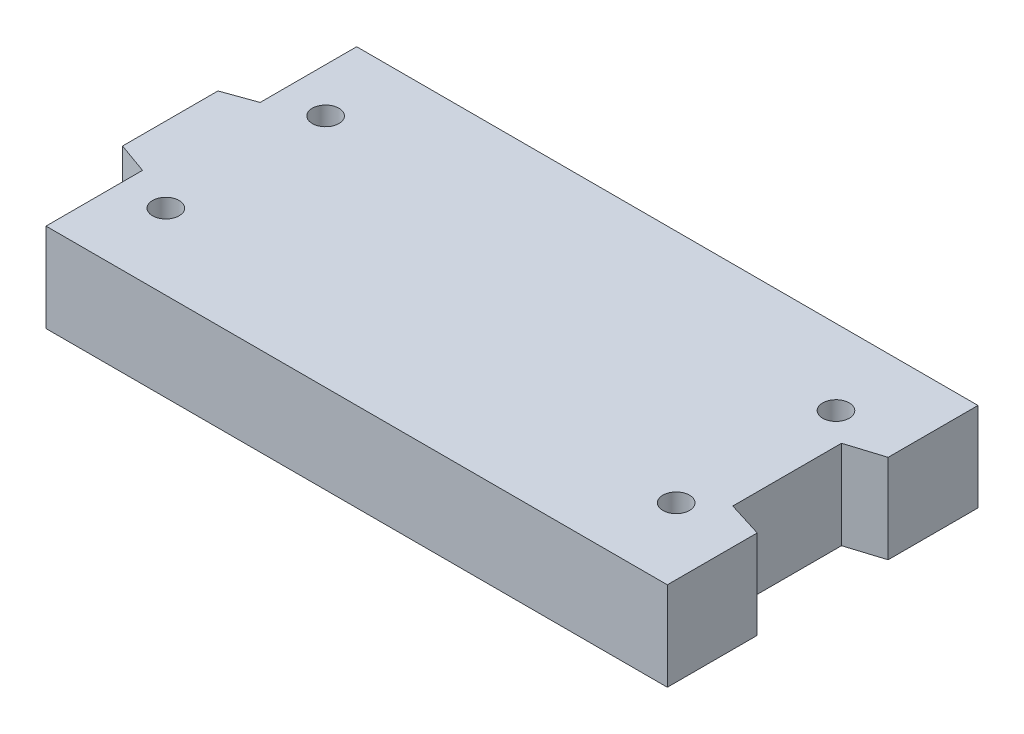
SolidWorks part; units mm, degrees
material "Carburized and nitrided special steel"
ref_plane "Piano frontale" through (0, 0, 0) normal (0, 0, 1) x (1, 0, 0)
ref_plane "Piano superiore" through (0, 0, 0) normal (0, 1, 0) x (1, 0, 0)
ref_plane "Piano destro" through (0, 0, 0) normal (1, 0, 0) x (0, 0, -1)
sketch "Schizzo2" plane through (0, 0, 0) normal (0, 1, 0) x (1, 0, 0)
  line L0 (-166.882, 0) -> (166.882, 0) construction
  line L1 (-162.6525, 21.5) -> (-162.6525, -21.5)
  line L2 (115.3475, 24.5) -> (115.3475, -24.5)
  line L3 (-144.6525, 70) -> (127.3475, 70)
  line L4 (131.3475, -29.5) -> (131.3475, -66)
  line L5 (-148.6525, -26.5) -> (-148.6525, -66)
  line L6 (-162.6525, 21.5) -> (-148.6525, 26.5)
  line L7 (115.3475, -24.5) -> (131.3475, -29.5)
  line L8 (115.3475, 24.5) -> (131.3475, 29.5)
  line L9 (-162.6525, -21.5) -> (-148.6525, -26.5)
  line L10 (-144.6525, -70) -> (127.3475, -70)
  line L11 (-148.6525, 26.5) -> (-148.6525, 66)
  line L12 (131.3475, 29.5) -> (131.3475, 66)
  line L13 (127.3475, 70) -> (131.3475, 70)
  line L14 (-148.6525, -66) -> (-148.6525, -70)
  line L15 (127.3475, -70) -> (131.3475, -70)
  line L16 (131.3475, -70) -> (131.3475, -66)
  line L17 (-144.6525, 70) -> (-148.6525, 70)
  line L18 (-148.6525, 70) -> (-148.6525, 66)
  line L19 (131.3475, 70) -> (131.3475, 66)
  line L20 (-148.6525, -70) -> (-144.6525, -70)
  point P1 (131.3475, 70)
  point P2 (-148.6525, 70)
  point P7 (-162.6525, 0)
  point P8 (131.3475, -70)
  point P13 (-148.6525, -70)
  point P15 (-162.6525, 0)
  point P17 (115.3475, 0)
  dimension "D1" = 70
  dimension "D2" = 26.5
  dimension "D3" = 21.5
  dimension "D4" = 280
  dimension "D5" = 16
  dimension "D6" = 24.5
  dimension "D7" = 29.5
  dimension "D8" = 14
extrude "Estrusione1" add sketch "Schizzo2" along normal blind 40
sketch "Schizzo5" plane through (0, 0, 0) normal (0, -1, 0) x (1, 0, 0)
  line L0 (-173.132, 0) -> (146.5535, 0) construction
  line L1 (-80.6525, 93.4302) -> (-80.6525, -110.732) construction
  line L4 (-148.6525, -70) -> (-148.6525, -26.5) construction
  circle A0 centre (-80.6525, 0) radius 40.25
  dimension "D1" = 68
extrude "Estrusione4" cut sketch "Schizzo5" against normal blind 12.5
draft "Sformo2" type of draft neutral plane draft angle 25 faces to draft 1 face at (-80.6525, 12.5, -40.25) neutral plane through (131.3475, 0, 29.5) neutral plane normal (0, -1, 0) parameters "D1"=25
fillet "Raccordo1" radius 3 1 edges at (-80.6525, 0, -40.25)
fillet "Raccordo2" radius 5 1 edges at (-80.6525, 12.5, -34.4212)
pattern_linear "Ripetizione a L1" count 2 spacing 141 along (1, 0, 0) of "Estrusione4", "Sformo2", "Raccordo1", "Raccordo2"
hole_wizard "M12 Tapped Hole1" positions "Schizzo3D1" profile "Schizzo8" tap size "M12" standard "ISO"
sketch3d "Schizzo3D1"
  line L0 (131.3475, 40, -70) -> (-148.6525, 40, -70) construction
  line L1 (-148.6525, 40, 70) -> (131.3475, 40, 70) construction
  line L2 (131.3475, 40, -29.5) -> (131.3475, 40, -70) construction
  line L3 (131.3475, 40, 70) -> (131.3475, 40, 29.5) construction
  point P0 (-128.6525, 40, -36)
  point P2 (101.3475, 40, -36)
  point P4 (101.3475, 40, 36)
  point P6 (-128.6525, 40, 36)
  dimension "D1" = 34
  dimension "D2" = 34
  dimension "D3" = 34
  dimension "D4" = 34
  dimension "D5" = 30
  dimension "D6" = 30
  dimension "D7" = 230
  dimension "D8" = 230
sketch "Schizzo8" plane through (-128.6525, 40, -36) normal (1, 0, 0) x (0, 0, 1)
  line L0 (0, 0) -> (0, 35.8144)
  line L1 (0, 35.8144) -> (5.1, 32.75)
  line L2 (5.1, 32.75) -> (5.1, 24)
  line L3 (5.1, 24) -> (6, 24)
  line L4 (6, 24) -> (6, 0)
  line L5 (6, 0) -> (0, 0)
  line L10 (0, 35.8144) -> (-5.1, 32.75) construction
  line L11 (0, -6.35) -> (0, 107.95) construction
  dimension "Tap Drill Dia." = 10.2
  dimension "Tap Drill Depth" = 32.75
  dimension "Thread Major Dia." = 12
  dimension "Thread Depth" = 24
  dimension "Drill Angle" = 118
